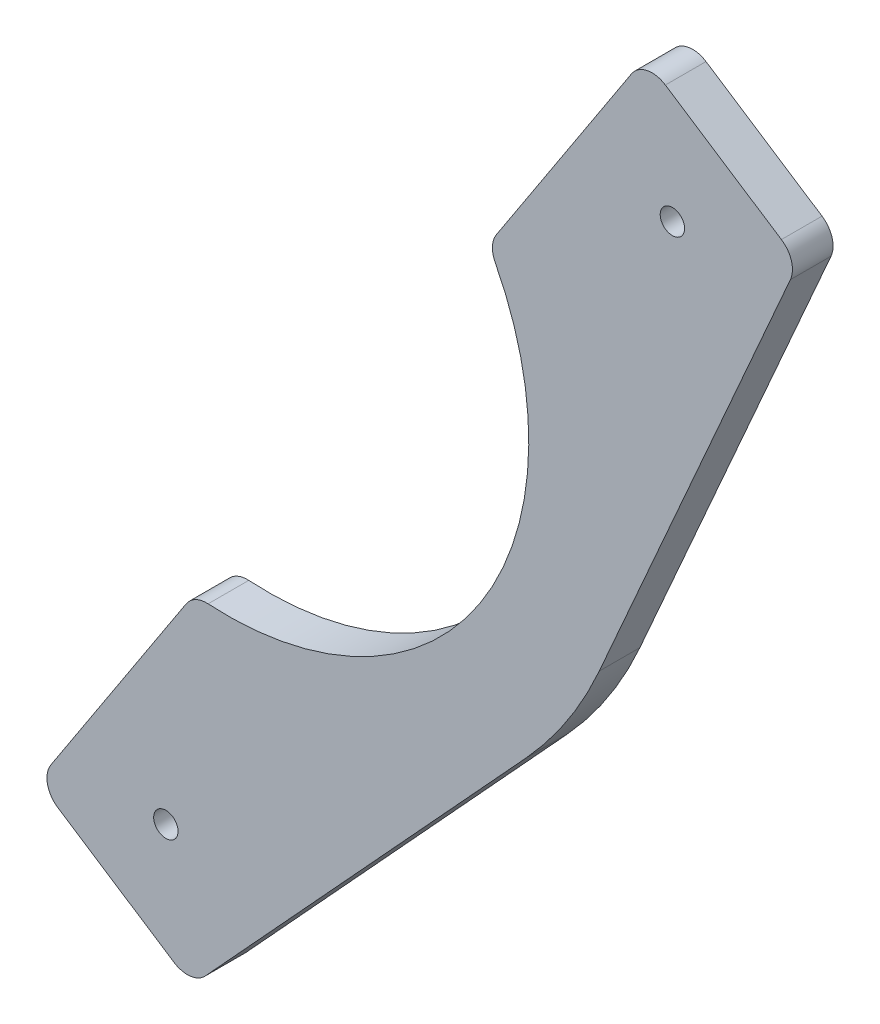
SolidWorks part; units mm, degrees
ref_plane "Front Plane" through (0, 0, 0) normal (0, 0, 1) x (1, 0, 0)
ref_plane "Top Plane" through (0, 0, 0) normal (0, 1, 0) x (1, 0, 0)
ref_plane "Right Plane" through (0, 0, 0) normal (1, 0, 0) x (0, 0, -1)
sketch "Sketch1" plane through (0, 0, 0) normal (0, 0, 1) x (1, 0, 0)
  line L0 (-68.1635, -46.3549) -> (-28.6392, -3.3312)
  line L1 (-19.6922, 10.3635) -> (3.8306, 63.8414)
  line L2 (2.7253, 67.5608) -> (-11.5553, 76.8907)
  line L3 (-15.7076, 76.02) -> (-32.3489, 50.5483)
  line L4 (-70.5236, -7.8829) -> (-87.1649, -33.3546)
  line L5 (-86.2942, -37.507) -> (-72.0136, -46.8368)
  line L6 (-23.6019, 3.1478) -> (-72.541, 35.121)
  circle A0 centre (-10.6893, 62.776) radius 1.5
  arc A1 (-28.6392, -3.3312) -> (-19.6922, 10.3635) centre (-65.4603, 30.495) ccw
  arc A2 (3.8306, 63.8414) -> (2.7253, 67.5608) centre (1.0845, 65.0493) ccw
  arc A3 (-11.5553, 76.8907) -> (-15.7076, 76.02) centre (-13.1961, 74.3792) ccw
  arc A4 (-32.3489, 50.5483) -> (-32.5025, 47.53) centre (-29.8374, 48.9075) ccw
  arc A5 (-67.8212, -6.5298) -> (-32.5025, 47.53) centre (-65.4603, 30.495) ccw
  arc A6 (-67.8212, -6.5298) -> (-70.5236, -7.8829) centre (-68.0121, -9.5237) ccw
  arc A7 (-87.1649, -33.3546) -> (-86.2942, -37.507) centre (-84.6534, -34.9955) ccw
  arc A8 (-72.0136, -46.8368) -> (-68.1635, -46.3549) centre (-70.3728, -44.3253) ccw
  circle A9 centre (-73.0205, -32.6301) radius 1.5
  spline S0 degree 1 poles (-71.4996, -48.4027) (-88.5331, -37.9079) knots 0 0 1 1
  spline S1 degree 1 poles (4.3658, 67.7191) (-12.0875, 79.1021) knots 0 0 1 1
extrude "Boss-Extrude1" add sketch "Sketch1" along normal blind 5 contours L5 A8 L0 A1 L6 A5 A6 L4 A7 A9 | A5 L6 A1 L1 A2 L2 A3 L3 A4 A0
